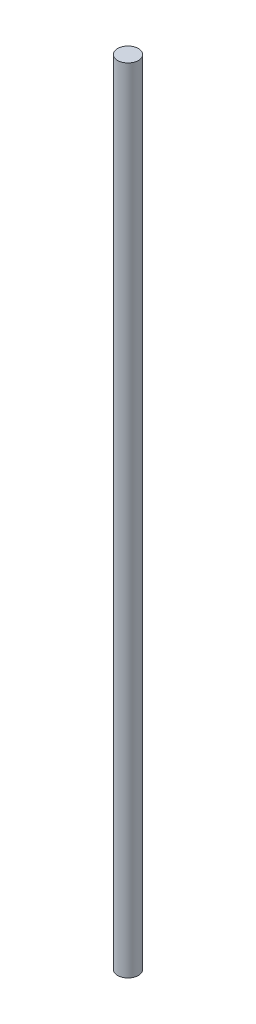
SolidWorks part; units mm, degrees
ref_plane "Front Plane" through (0, 0, 0) normal (0, 0, 1) x (1, 0, 0)
ref_plane "Top Plane" through (0, 0, 0) normal (0, 1, 0) x (1, 0, 0)
ref_plane "Right Plane" through (0, 0, 0) normal (1, 0, 0) x (0, 0, -1)
sketch "Sketch1" plane through (0, 0, 0) normal (0, 1, 0) x (1, 0, 0)
  circle A0 centre (0, 0) radius 4
extrude "Boss-Extrude1" add sketch "Sketch1" along normal blind 305
